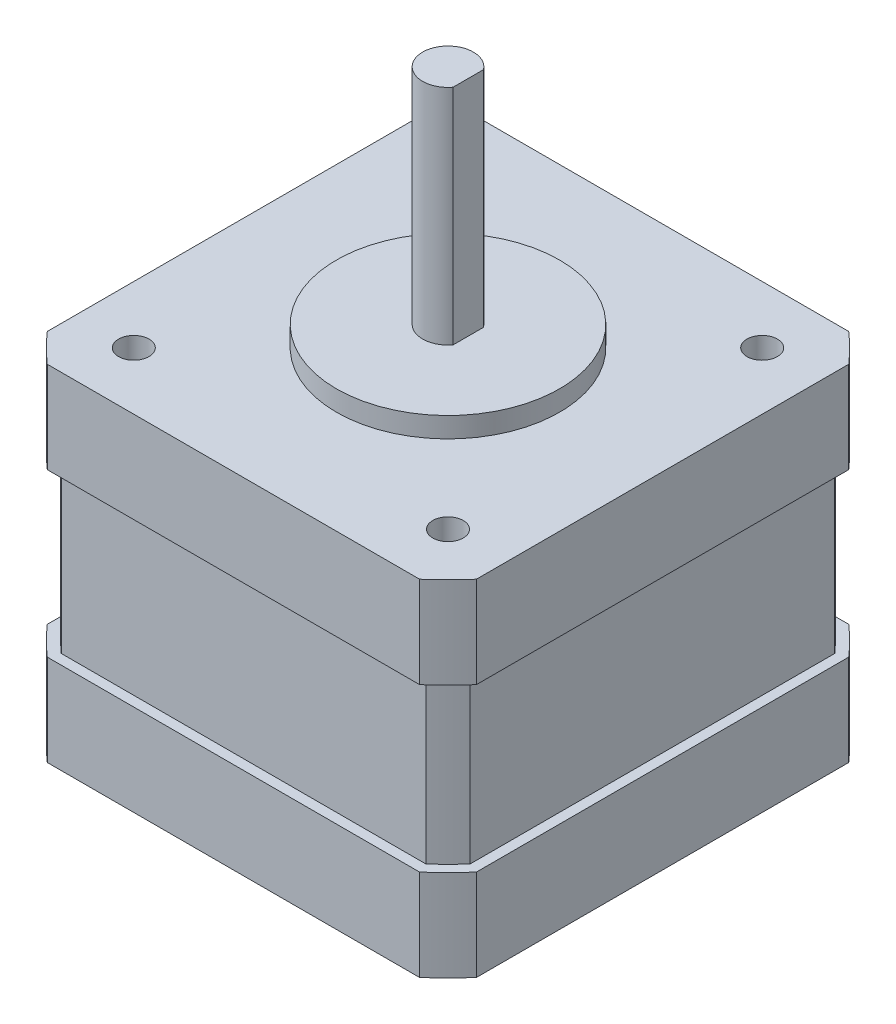
SolidWorks part; units mm, degrees
ref_plane "Front Plane" through (0, 0, 0) normal (0, 0, 1) x (1, 0, 0)
ref_plane "Top Plane" through (0, 0, 0) normal (0, 1, 0) x (1, 0, 0)
ref_plane "Right Plane" through (0, 0, 0) normal (1, 0, 0) x (0, 0, -1)
sketch "Sketch1" plane through (0, 0, 0) normal (0, 1, 0) x (1, 0, 0)
  line L0 (2, 1.5) -> (2, -1.5)
  line L1 (0, 5.0754) -> (0, -7.1941) construction
  arc A0 (2, 1.5) -> (2, -1.5) centre (0, 0) ccw
  dimension "D1" = 2
extrude "Boss-Extrude1" add sketch "Sketch1" along normal blind 24
sketch "Sketch2" plane through (0, 0, 0) normal (0, 1, 0) x (1, 0, 0)
  circle A0 centre (0, 0) radius 11
extrude "Boss-Extrude2" add sketch "Sketch2" along normal blind 2
sketch "Sketch3" plane through (0, 0, 0) normal (0, 1, 0) x (1, 0, 0)
  line L1 (-18.3488, 21.15) -> (18.3488, 21.15)
  line L2 (-21.15, 18.3488) -> (-21.15, -18.3488)
  line L3 (-18.3488, -21.15) -> (18.3488, -21.15)
  line L4 (21.15, 18.3488) -> (21.15, -18.3488)
  line L5 (-21.15, 21.15) -> (21.15, -21.15) construction
  line L6 (-21.15, -21.15) -> (21.15, 21.15) construction
  arc A0 (-21.15, -18.3488) -> (-18.3488, -21.15) centre (0, 0) ccw
  circle A1 centre (0, 0) radius 21.9 construction
  arc A2 (-18.3488, 21.15) -> (-21.15, 18.3488) centre (0, 0) ccw
  arc A3 (18.3488, -21.15) -> (21.15, -18.3488) centre (0, 0) ccw
  arc A4 (21.15, 18.3488) -> (18.3488, 21.15) centre (0, 0) ccw
  point P0 (0, 0)
  dimension "D1" = 42.3
  dimension "D2" = 42.3
extrude "Boss-Extrude3" add sketch "Sketch3" against normal blind 9
sketch "Sketch4" plane through (0, -9, 0) normal (0, -1, 0) x (1, 0, 0)
  line L8 (20.15, -17.9716) -> (20.15, 17.9716)
  line L9 (17.9716, 20.15) -> (-17.9716, 20.15)
  line L10 (-20.15, 17.9716) -> (-20.15, -17.9716)
  line L11 (-17.9716, -20.15) -> (17.9716, -20.15)
  line L12 (20.15, -17.9716) -> (20.15, 17.9716)
  line L13 (17.9716, 20.15) -> (-17.9716, 20.15)
  line L14 (-20.15, 17.9716) -> (-20.15, -17.9716)
  line L15 (-17.9716, -20.15) -> (17.9716, -20.15)
  arc A8 (17.9716, -20.15) -> (20.15, -17.9716) centre (0, 0) ccw
  arc A9 (20.15, 17.9716) -> (17.9716, 20.15) centre (0, 0) ccw
  arc A10 (-17.9716, 20.15) -> (-20.15, 17.9716) centre (0, 0) ccw
  arc A11 (-20.15, -17.9716) -> (-17.9716, -20.15) centre (0, 0) ccw
  arc A12 (17.9716, -20.15) -> (20.15, -17.9716) centre (0, 0) ccw
  arc A13 (20.15, 17.9716) -> (17.9716, 20.15) centre (0, 0) ccw
  arc A14 (-17.9716, 20.15) -> (-20.15, 17.9716) centre (0, 0) ccw
  arc A15 (-20.15, -17.9716) -> (-17.9716, -20.15) centre (0, 0) ccw
  dimension "D1" = 1
extrude "Boss-Extrude4" add sketch "Sketch4" along normal blind 16
sketch "Sketch5" plane through (0, -25, 0) normal (0, -1, 0) x (1, 0, 0)
  line L8 (21.15, -18.3488) -> (21.15, 18.3488)
  line L9 (18.3488, 21.15) -> (-18.3488, 21.15)
  line L10 (-21.15, 18.3488) -> (-21.15, -18.3488)
  line L11 (-18.3488, -21.15) -> (18.3488, -21.15)
  line L12 (21.15, -18.3488) -> (21.15, 18.3488)
  line L13 (18.3488, 21.15) -> (-18.3488, 21.15)
  line L14 (-21.15, 18.3488) -> (-21.15, -18.3488)
  line L15 (-18.3488, -21.15) -> (18.3488, -21.15)
  arc A8 (18.3488, -21.15) -> (21.15, -18.3488) centre (0, 0) ccw
  arc A9 (21.15, 18.3488) -> (18.3488, 21.15) centre (0, 0) ccw
  arc A10 (-18.3488, 21.15) -> (-21.15, 18.3488) centre (0, 0) ccw
  arc A11 (-21.15, -18.3488) -> (-18.3488, -21.15) centre (0, 0) ccw
  arc A12 (18.3488, -21.15) -> (21.15, -18.3488) centre (0, 0) ccw
  arc A13 (21.15, 18.3488) -> (18.3488, 21.15) centre (0, 0) ccw
  arc A14 (-18.3488, 21.15) -> (-21.15, 18.3488) centre (0, 0) ccw
  arc A15 (-21.15, -18.3488) -> (-18.3488, -21.15) centre (0, 0) ccw
  dimension "D1" = 1
extrude "Boss-Extrude5" add sketch "Sketch5" along normal blind 9
sketch "Sketch6" plane through (0, 0, 0) normal (0, 1, 0) x (1, 0, 0)
  line L0 (-19.799, -19.799) -> (19.799, 19.799) construction
  line L1 (19.799, -19.799) -> (-19.799, 19.799) construction
  arc A0 (-21.15, -18.3488) -> (-18.3488, -21.15) centre (0, 0) ccw construction
  arc A1 (21.15, 18.3488) -> (18.3488, 21.15) centre (0, 0) ccw construction
  arc A2 (18.3488, -21.15) -> (21.15, -18.3488) centre (0, 0) ccw construction
  arc A3 (-18.3488, 21.15) -> (-21.15, 18.3488) centre (0, 0) ccw construction
  circle A4 centre (0, 0) radius 21.9 construction
  circle A5 centre (-15.4856, 15.4856) radius 1.5
  circle A6 centre (15.4856, 15.4856) radius 1.5
  circle A7 centre (15.4856, -15.4856) radius 1.5
  circle A8 centre (-15.4856, -15.4856) radius 1.5
  point P30 (0, 0)
  dimension "D1" = 4
extrude "Cut-Extrude1" cut sketch "Sketch6" against normal blind 4.5
